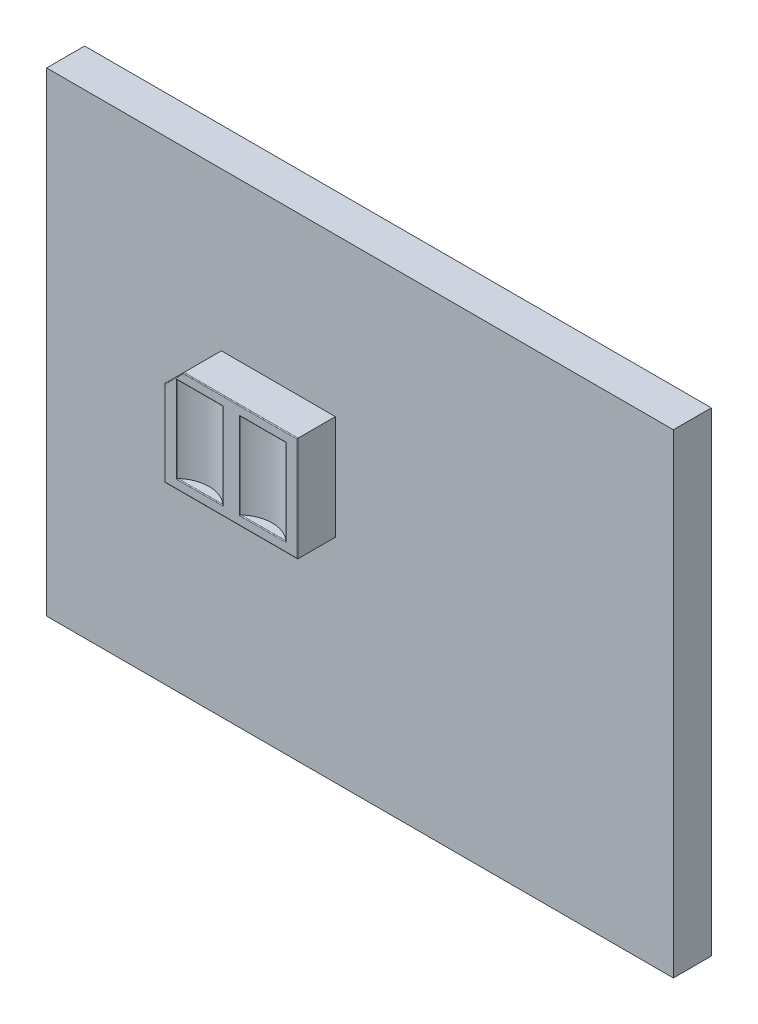
SolidWorks part; units mm, degrees
ref_plane "Face" through (0, 0, 0) normal (0, 0, 1) x (1, 0, 0)
ref_plane "Dessus" through (0, 0, 0) normal (0, 1, 0) x (1, 0, 0)
ref_plane "Droite" through (0, 0, 0) normal (1, 0, 0) x (0, 0, -1)
sketch "Esquisse1" plane through (0, 0, 0) normal (0, 0, 1) x (1, 0, 0)
  line L1 (-8.25, 6.25) -> (8.25, 6.25)
  line L2 (-8.25, 6.25) -> (-8.25, -6.25)
  line L3 (-8.25, -6.25) -> (8.25, -6.25)
  line L4 (8.25, 6.25) -> (8.25, -6.25)
  dimension "D1" = 6.25
  dimension "D2" = 12.5
  dimension "D3" = 8.25
  dimension "D4" = 16.5
extrude "Extrusion1" add sketch "Esquisse1" along normal blind 1
sketch "Esquisse5"
sketch "Esquisse3" plane through (0, 0, 0) normal (0, 0, 1) x (1, 0, 0)
  line L0 (-3.65, 2.1) -> (-0.65, 2.1)
  line L1 (-0.65, 2.1) -> (-0.65, -0.65)
  line L2 (-4.15, 1.6) -> (-3.65, 2.1)
  line L3 (-0.65, -0.65) -> (-4.15, -0.65)
  line L4 (-4.15, -0.65) -> (-4.15, 1.6)
  line L5 (-8.25, -6.25) -> (8.25, -6.25) construction
  line L6 (8.25, -6.25) -> (8.25, 6.25) construction
  point P0 (-4.15, 2.1)
  dimension "D1" = 5.6
  dimension "D3" = 3.5
  dimension "D4" = 8.9
extrude "Extrusion2" add sketch "Esquisse3" along normal blind 2
ref_plane "Plan1" through (0, -0.4, 0) normal (0, -1, 0) x (1, 0, 0)
sketch "Esquisse4" plane through (0, -0.4, 0) normal (0, -1, 0) x (1, 0, 0)
  line L0 (-2.3878, 2.8941) -> (-2.3878, -0.6438) construction
  line L2 (-4.15, 2) -> (-0.65, 2) construction
  line L3 (-2.1682, 2) -> (-0.948, 2)
  line L4 (-3.65, 2) -> (-4.15, 2) construction
  line L5 (-2.6074, 2) -> (-3.8276, 2)
  arc A0 (-3.8276, 2) -> (-2.6074, 2) centre (-3.2175, 2.6375) ccw
  arc A1 (-0.948, 2) -> (-2.1682, 2) centre (-1.5581, 2.6375) cw
extrude "Enlèv. mat.-Extru.1" cut sketch "Esquisse4" against normal blind 2.25
fillet "Congé1" radius 0.02
